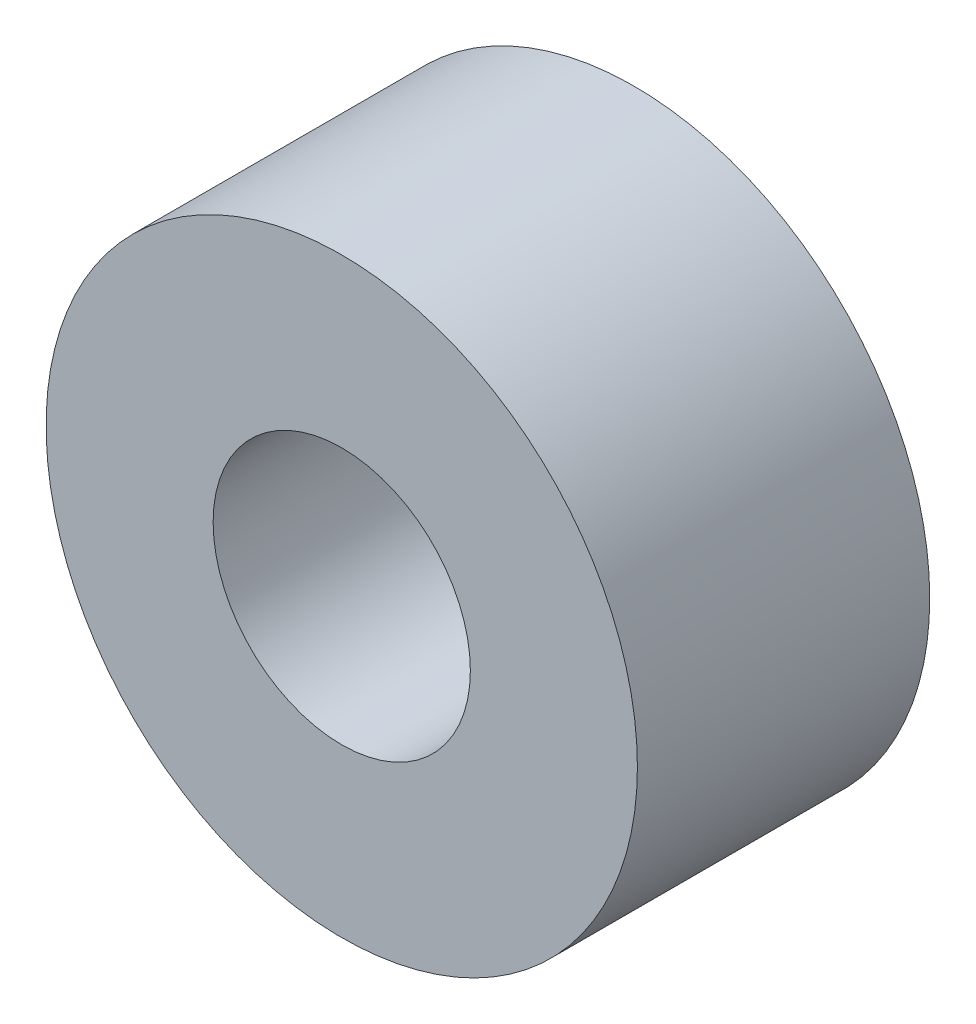
SolidWorks part; units mm, degrees
ref_plane "Front Plane" through (0, 0, 0) normal (0, 0, 1) x (1, 0, 0)
ref_plane "Top Plane" through (0, 0, 0) normal (0, 1, 0) x (1, 0, 0)
ref_plane "Right Plane" through (0, 0, 0) normal (1, 0, 0) x (0, 0, -1)
sketch "Sketch1" plane through (0, 0, 0) normal (0, 0, 1) x (1, 0, 0)
  circle A0 centre (0, 0) radius 4.8895
  circle A1 centre (0, 0) radius 11.2395
  dimension "D1" = 9.779
  dimension "D2" = 6.35
extrude "Boss-Extrude1" add sketch "Sketch1" along normal blind 11.1125
